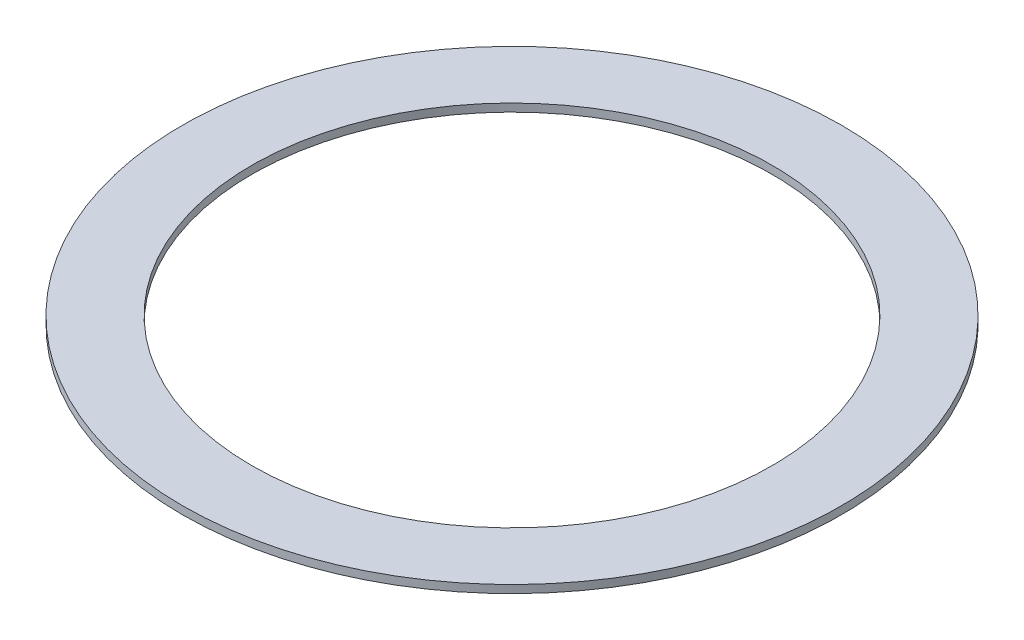
SolidWorks part; units mm, degrees
ref_plane "Front Plane" through (0, 0, 0) normal (0, 0, 1) x (1, 0, 0)
ref_plane "Top Plane" through (0, 0, 0) normal (0, 1, 0) x (1, 0, 0)
ref_plane "Right Plane" through (0, 0, 0) normal (1, 0, 0) x (0, 0, -1)
sketch "Sketch1" plane through (0, 0, 0) normal (0, 1, 0) x (1, 0, 0)
  circle A0 centre (0, 0) radius 16.5
  circle A1 centre (0, 0) radius 20.9
  dimension "D1" = 33
  dimension "D2" = 41.8
extrude "Boss-Extrude1" add sketch "Sketch1" along normal blind 0.5
equation "\"Housing_OD\"= 45mm"
equation "\"Housing_Wall\"= 1.5mm"
equation "\"Stack_ID\"= 28mm"
equation "\"Ampoule_OD\"= 25.5mm"
equation "\"Cell_Height\"= 1.66mm"
equation "\"D2@Sketch1\"=\"Housing_OD\" - (2 * \"Housing_Wall\") - 0.2mm"
